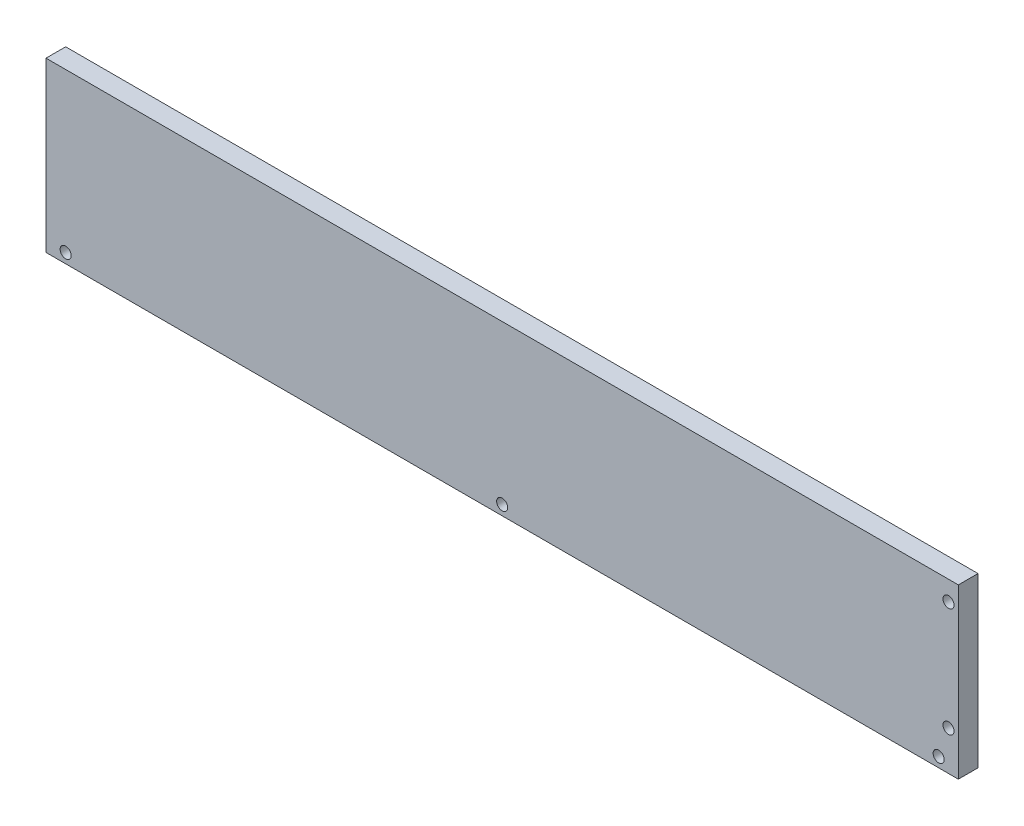
SolidWorks part; units mm, degrees
ref_plane "Front Plane" through (0, 0, 0) normal (0, 0, 1) x (1, 0, 0)
ref_plane "Top Plane" through (0, 0, 0) normal (0, 1, 0) x (1, 0, 0)
ref_plane "Right Plane" through (0, 0, 0) normal (1, 0, 0) x (0, 0, -1)
sketch "Sketch1" plane through (0, 0, 0) normal (0, 0, 1) x (1, 0, 0)
  line L0 (-288.29, 3.175) -> (-147.32, 3.175) construction
  line L1 (-147.32, 3.175) -> (-6.35, 3.175) construction
  line L2 (-3.175, 48) -> (-3.175, 12.7) construction
  circle A0 centre (-3.175, 48) radius 1.7859
  circle A1 centre (-3.175, 12.7) radius 1.7859
  circle A2 centre (-6.35, 3.175) radius 1.7859
  circle A3 centre (-147.32, 3.175) radius 1.7859
  circle A4 centre (-288.29, 3.175) radius 1.7859
  point P11 (-162.1456, 3.175)
  line B0 (0, 0) -> (0, 54.35)
  line B1 (0, 54.35) -> (-294.64, 54.35)
  line B2 (-294.64, 54.35) -> (-294.64, 0)
  line B3 (-294.64, 0) -> (0, 0)
  dimension "D3" = 3.5719
  dimension "D1" = 3.175
  dimension "D2" = 6.35
  dimension "D4" = 6.35
  dimension "D5" = 6.35
  dimension "D6" = 3.175
  dimension "D7" = 12.7
sketch_block_instance "Right_Side-1"
sketch_block "Right_Side"
extrude "Boss-Extrude1" add sketch "Sketch1" along normal blind 6.35
